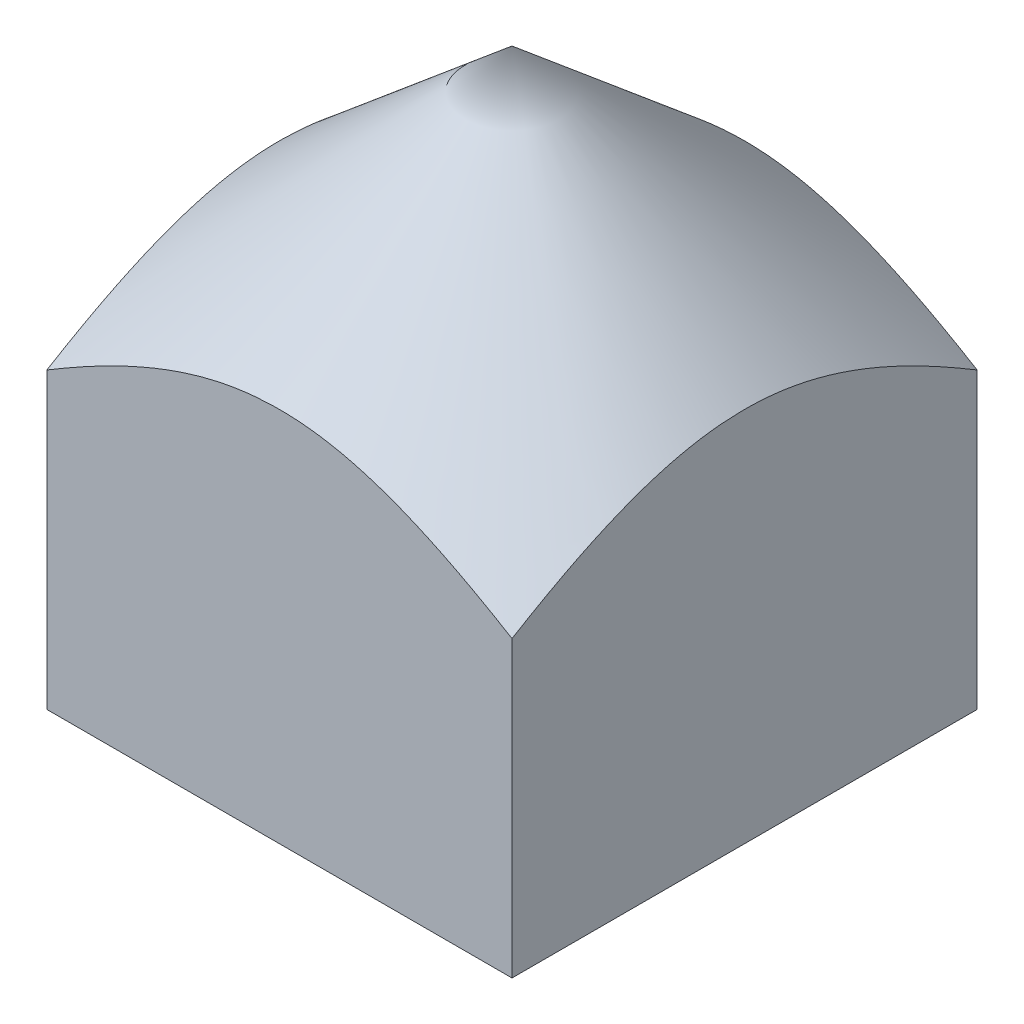
SolidWorks part; units mm, degrees
ref_plane "Plano frontal" through (0, 0, 0) normal (0, 0, 1) x (1, 0, 0)
ref_plane "Plano superior" through (0, 0, 0) normal (0, 1, 0) x (1, 0, 0)
ref_plane "Plano direito" through (0, 0, 0) normal (1, 0, 0) x (0, 0, -1)
sketch "Esboço1" plane through (0, 0, 0) normal (0, 1, 0) x (1, 0, 0)
  line L1 (30, 30) -> (-30, 30)
  line L2 (30, 30) -> (30, -30)
  line L3 (30, -30) -> (-30, -30)
  line L4 (-30, 30) -> (-30, -30)
  line L5 (30, 30) -> (-30, -30) construction
  line L6 (30, -30) -> (-30, 30) construction
  point P0 (0, 0)
  dimension "D1" = 60
extrude "Ressalto-extrusão1" add sketch "Esboço1" along normal blind 80
sketch "Esboço2" plane through (0, 0, 0) normal (0, 0, 1) x (1, 0, 0)
  line L0 (0, 88.5906) -> (0, 74.1116)
  line L1 (0, 74.1116) -> (56.9981, 25.4874)
  line L2 (56.9981, 25.4874) -> (56.9981, 88.5906)
  line L3 (56.9981, 88.5906) -> (0, 88.5906)
  point P3 (42.1366, 48.4631)
  point P6 (0, 79.3481)
  point P7 (0, 75.7146)
  point P8 (0, 74.1116)
  point P9 (41.7091, 43.5472)
  point P10 (0, 0)
  point P11 (41.1748, 37.6694)
  point P12 (41.7091, 55.7302)
  point P13 (51.4341, 45.1502)
  point P14 (60.1928, 39.9249)
  point P15 (56.9981, 25.4874)
revolve "Corte-Revolução7" cut sketch "Esboço2" angle 360 about L0
